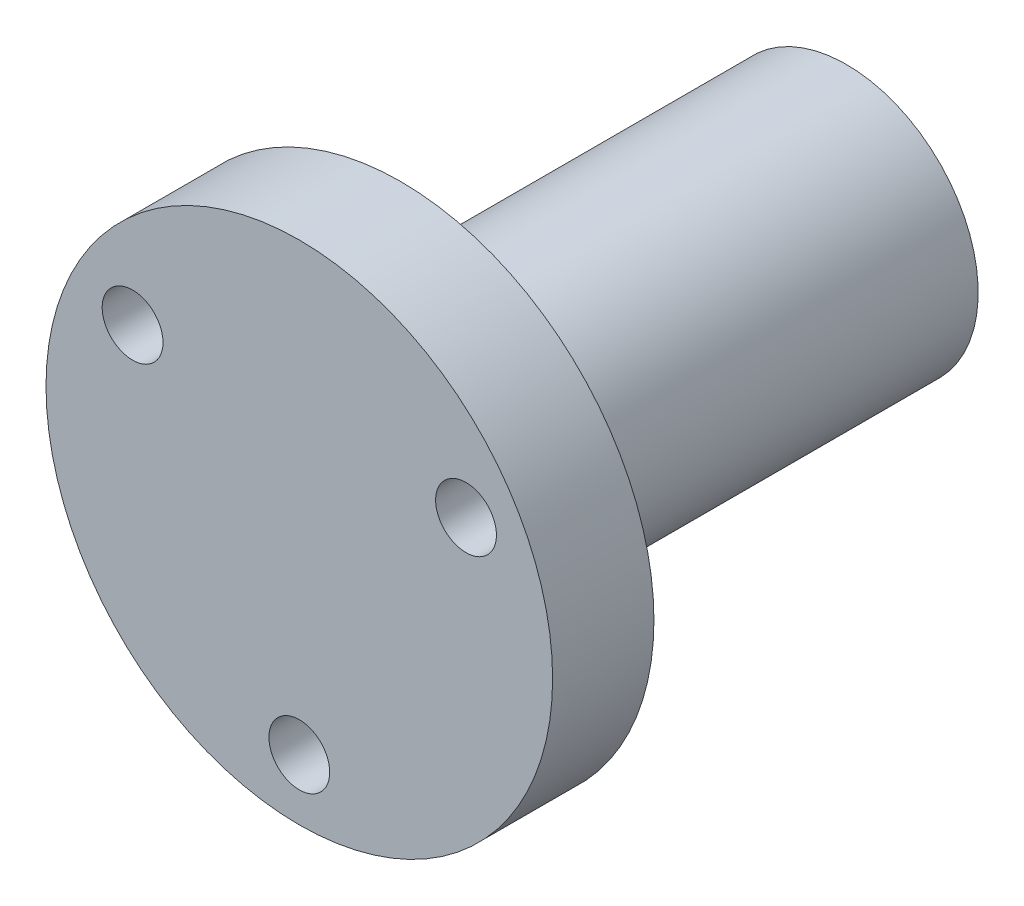
SolidWorks part; units mm, degrees
ref_plane "Front Plane" through (0, 0, 0) normal (0, 0, 1) x (1, 0, 0)
ref_plane "Top Plane" through (0, 0, 0) normal (0, 1, 0) x (1, 0, 0)
ref_plane "Right Plane" through (0, 0, 0) normal (1, 0, 0) x (0, 0, -1)
sketch "Sketch1" plane through (0, 0, 0) normal (0, 0, 1) x (1, 0, 0)
  circle A0 centre (0, 0) radius 12.5
  dimension "D1" = 25
extrude "Boss-Extrude1" add sketch "Sketch1" against normal blind 5
sketch "Sketch2" plane through (0, 0, -5) normal (0, 0, -1) x (-1, 0, 0)
  circle A0 centre (0, 0) radius 6.5
  dimension "D1" = 13
extrude "Boss-Extrude2" add sketch "Sketch2" along normal blind 22
sketch "Sketch3" plane through (0, 0, -27) normal (0, 0, -1) x (-1, 0, 0)
  line L0 (-1.6613, -2) -> (1.6613, -2) construction
  line L1 (-1.7664, -2.3) -> (1.7664, -2.3)
  arc A0 (1.6613, -2) -> (-1.6613, -2) centre (0, 0) ccw construction
  arc A1 (1.7664, -2.3) -> (-1.7664, -2.3) centre (0, 0) ccw
  dimension "D1" = 5.2
  dimension "D2" = 2
  dimension "D3" = 0.3
extrude "Cut-Extrude1" cut sketch "Sketch3" against normal blind 22
sketch "Sketch4" plane through (0, 0, 0) normal (0, 0, 1) x (1, 0, 0)
  line L0 (0, 0) -> (-8.2272, 4.75) construction
  line L1 (0, 0) -> (-12.5, 0) construction
  line L2 (0, 0) -> (8.2272, 4.75) construction
  line L3 (0, 0) -> (0, -9.5) construction
  line L4 (0, 0) -> (-8.2272, 4.75) construction
  line L5 (0, 0) -> (8.2272, 4.75) construction
  circle A0 centre (-8.2272, 4.75) radius 1.5
  circle A1 centre (0, 0) radius 12.5 construction
  circle A2 centre (8.2272, 4.75) radius 1.5
  circle A3 centre (0, -9.5) radius 1.5
  dimension "D2" = 3
  dimension "D1" = 30
  dimension "D3" = 9.5
  dimension "D5" = 120
  dimension "D4" = 3
extrude "Cut-Extrude2" cut sketch "Sketch4" against normal up to next
